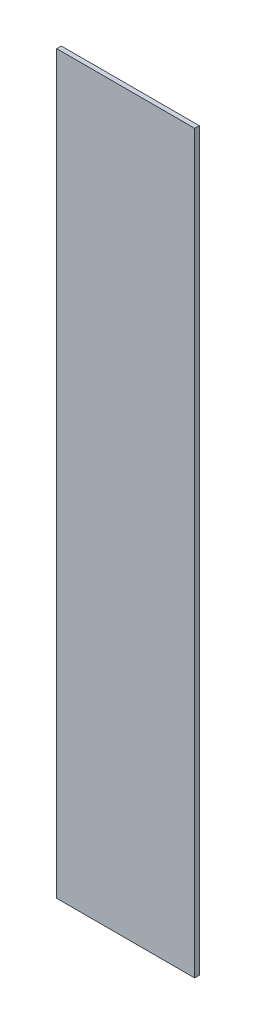
SolidWorks part; units mm, degrees
ref_plane "Plan de face" through (0, 0, 0) normal (0, 0, 1) x (1, 0, 0)
ref_plane "Plan de dessus" through (0, 0, 0) normal (0, 1, 0) x (1, 0, 0)
ref_plane "Plan de droite" through (0, 0, 0) normal (1, 0, 0) x (0, 0, -1)
sketch "Esquisse1" plane through (0, 0, 0) normal (0, 0, 1) x (1, 0, 0)
  line L1 (-75, 400) -> (75, 400)
  line L2 (-75, 400) -> (-75, -400)
  line L3 (-75, -400) -> (75, -400)
  line L4 (75, 400) -> (75, -400)
  line L5 (-75, 400) -> (75, -400) construction
  line L6 (-75, -400) -> (75, 400) construction
  point P0 (0, 0)
  dimension "D1" = 150
  dimension "D2" = 800
extrude "Boss.-Extru.1" add sketch "Esquisse1" along normal blind 5
